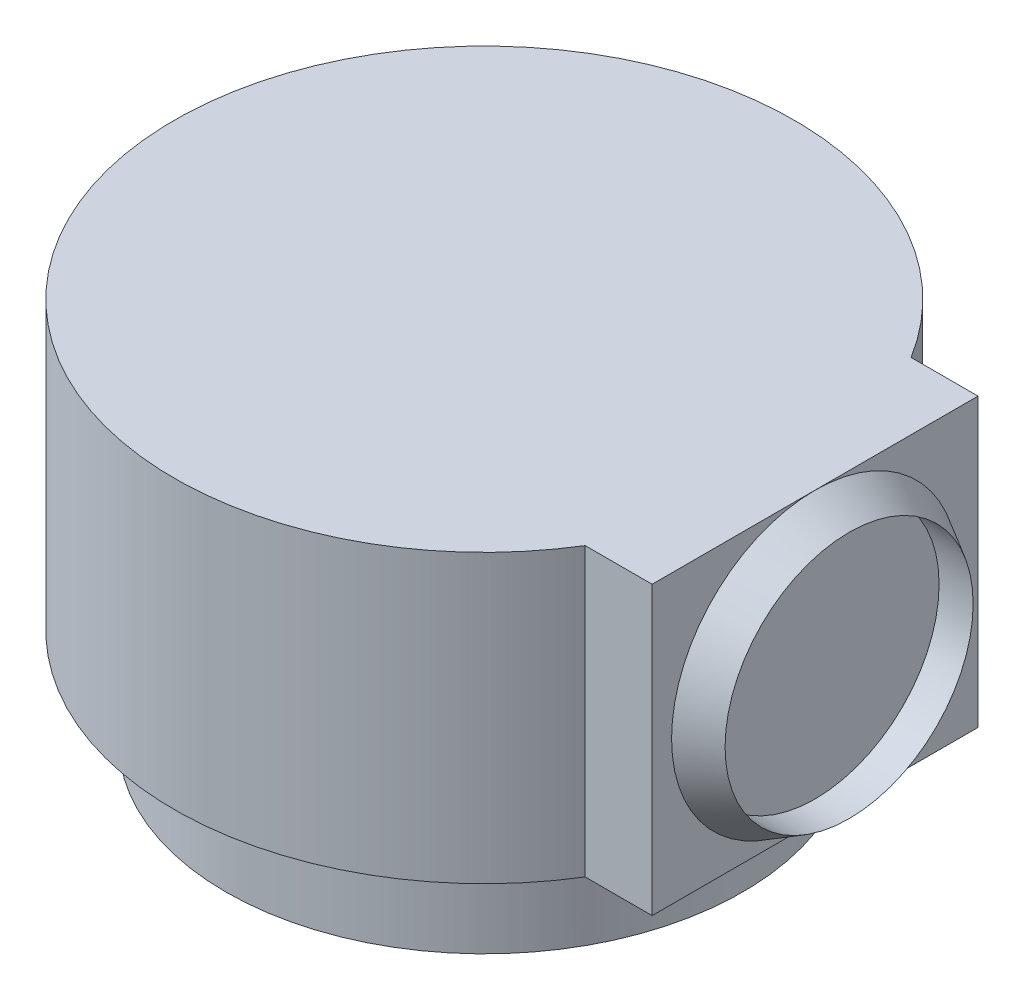
SolidWorks part; units mm, degrees
ref_plane "Front Plane" through (0, 0, 0) normal (0, 0, 1) x (1, 0, 0)
ref_plane "Top Plane" through (0, 0, 0) normal (0, 1, 0) x (1, 0, 0)
ref_plane "Right Plane" through (0, 0, 0) normal (1, 0, 0) x (0, 0, -1)
sketch "Sketch1" plane through (0, 0, 0) normal (0, 1, 0) x (1, 0, 0)
  circle A0 centre (0, 0) radius 159.375
extrude "Boss-Extrude1" add sketch "Sketch1" along normal blind 147.5
sketch "Sketch2" plane through (0, 0, 0) normal (1, 0, 0) x (0, 0, -1)
  line L1 (159.375, 147.5) -> (-159.375, 147.5) construction
  line L3 (-83.75, 147.5) -> (-83.75, 0)
  line L4 (-159.375, 0) -> (159.375, 0) construction
  line L5 (-83.75, 0) -> (83.75, 0)
  line L6 (83.75, 0) -> (83.75, 147.5)
  line L7 (83.75, 147.5) -> (-83.75, 147.5)
extrude "Boss-Extrude2" add sketch "Sketch2" along normal blind 170
sketch "Sketch3" plane through (170, 0, 0) normal (1, 0, 0) x (0, 0, -1)
  line L0 (0, 0) -> (0, 20) construction
  line L1 (-83.75, 0) -> (83.75, 0) construction
sketch "Sketch4" plane through (0, 0, 0) normal (0, 0, 1) x (1, 0, 0)
  line L0 (170, 0) -> (170, 10)
  line L1 (170, 0) -> (170, 20) construction
  line L2 (170, 0) -> (170, 147.5) construction
  line L3 (170, 10) -> (187.5, 10)
  line L4 (187.5, 10) -> (170, 0)
  line L5 (170, 0) -> (170, 73.75) construction
  line L6 (170, 73.75) -> (215.633, 73.75) construction
revolve "Revolve1" add sketch "Sketch4" angle 360 about L6
sketch "Sketch5" plane through (0, 0, 0) normal (0, -1, 0) x (-1, 0, 0)
  circle A0 centre (0, 0) radius 132.8125
extrude "Boss-Extrude3" add sketch "Sketch5" along normal blind 50
